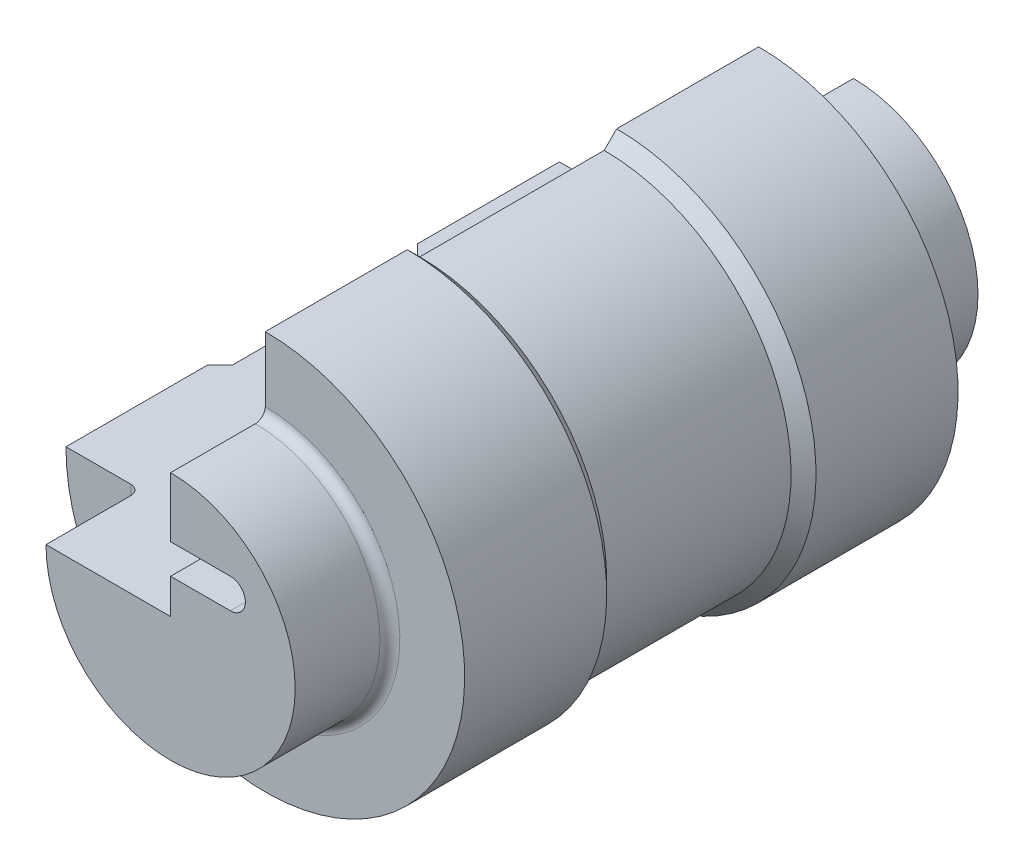
SolidWorks part; units mm, degrees
material "AISI 1020"
ref_plane "Plan de face" through (0, 0, 0) normal (0, 0, 1) x (1, 0, 0)
ref_plane "Plan de dessus" through (0, 0, 0) normal (0, 1, 0) x (1, 0, 0)
ref_plane "Plan de droite" through (0, 0, 0) normal (1, 0, 0) x (0, 0, -1)
sketch "Esquisse1" plane through (0, 0, 0) normal (1, 0, 0) x (0, 0, -1)
  line L0 (-68.5, 0) -> (68.5, 0)
  line L1 (44, 0) -> (-44, 0) construction
  line L2 (68.5, 0) -> (68.5, 25)
  line L3 (68.5, 25) -> (51.5, 25)
  line L4 (49.5, 27) -> (49.5, 40)
  line L5 (49.5, 40) -> (21, 40)
  line L6 (21, 40) -> (18.5, 37.5)
  line L7 (18.5, 37.5) -> (-18.5, 37.5)
  line L8 (0, 44) -> (0, -44) construction
  line L9 (-21, 40) -> (-18.5, 37.5)
  line L10 (-49.5, 40) -> (-21, 40)
  line L11 (-49.5, 27) -> (-49.5, 40)
  line L12 (-68.5, 25) -> (-51.5, 25)
  line L13 (-68.5, 0) -> (-68.5, 25)
  arc A0 (51.5, 25) -> (49.5, 27) centre (51.5, 27) cw
  arc A1 (-49.5, 27) -> (-51.5, 25) centre (-51.5, 27) cw
  point P14 (0, 37.5)
  point P19 (0, 0)
  point P22 (49.5, 25)
  point P25 (-49.5, 25)
  dimension "D6" = 2
  dimension "D7" = 2
  dimension "D1" = 25
  dimension "D2" = 40
  dimension "D3" = 19
  dimension "D4" = 28.5
  dimension "D5" = 137
  dimension "D8" = 2.5
  dimension "D9" = 135
revolve "Révolution1" add sketch "Esquisse1" angle 360 about L0
sketch "Esquisse3" plane through (0, 0, 0) normal (0, 0, 1) x (1, 0, 0)
  line L1 (0, 0) -> (-49.5903, 0)
  line L2 (0, 0) -> (0, 55.3279)
  line L3 (0, 55.3279) -> (-49.5903, 55.3279)
  line L4 (-49.5903, 0) -> (-49.5903, 55.3279)
extrude "Enlèv. mat.-Extru.1" cut sketch "Esquisse3" against normal through all both and the other way through all
sketch "Esquisse4" plane through (0, 0, 0) normal (0, 0, 1) x (1, 0, 0)
  line L0 (0, 0) -> (0, 7)
  line L1 (0, -52.4303) -> (0, 52.4303) construction
  line L2 (0, 7) -> (12, 7)
  line L3 (12, 13) -> (0, 13)
  line L4 (49.2747, 0) -> (-49.2747, 0) construction
  line L5 (0, 13) -> (0, 7)
  arc A0 (12, 7) -> (12, 13) centre (12, 10) ccw
  dimension "D3" = 3
  dimension "D1" = 12
  dimension "D2" = 7
extrude "Enlèv. mat.-Extru.2" cut sketch "Esquisse4" against normal through all both and the other way through all contours L2 A0 L3 L5
equation "\"A\" = 137"
equation "\"B\" = 19"
equation "\"C\" = 28.5"
equation "\"D3@Esquisse1\"=\"B\""
equation "\"D4@Esquisse1\"= \"C\""
equation "\"D5@Esquisse1\"=\"A\""
